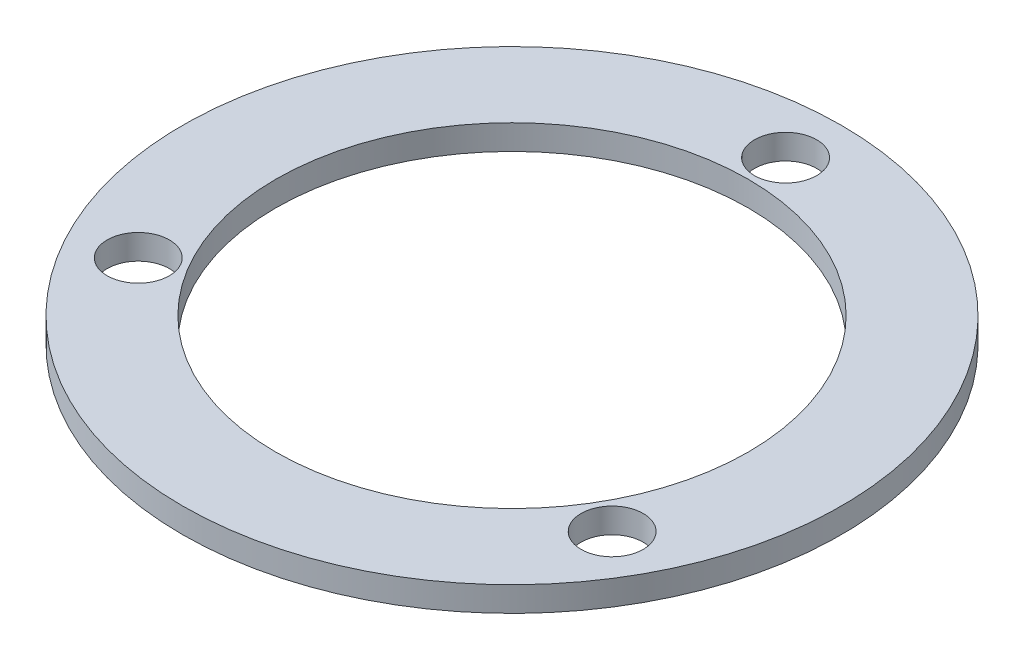
SolidWorks part; units mm, degrees
ref_plane "Front Plane" through (0, 0, 0) normal (0, 0, 1) x (1, 0, 0)
ref_plane "Top Plane" through (0, 0, 0) normal (0, 1, 0) x (1, 0, 0)
ref_plane "Right Plane" through (0, 0, 0) normal (1, 0, 0) x (0, 0, -1)
sketch "Sketch1" plane through (0, 0, 0) normal (0, 1, 0) x (1, 0, 0)
  circle A0 centre (0, 0) radius 9.5
  circle A1 centre (0, 0) radius 13.25
  circle A2 centre (0, 11) radius 1.25
  circle A3 centre (9.5263, -5.5) radius 1.25
  circle A4 centre (-9.5263, -5.5) radius 1.25
  point P12 (0, 0)
  dimension "D1" = 19
  dimension "D2" = 26.5
  dimension "D4" = 2.5
  dimension "D3" = 11
  dimension "D5" = 3
extrude "Boss-Extrude1" add sketch "Sketch1" along normal blind 1 contours A1
